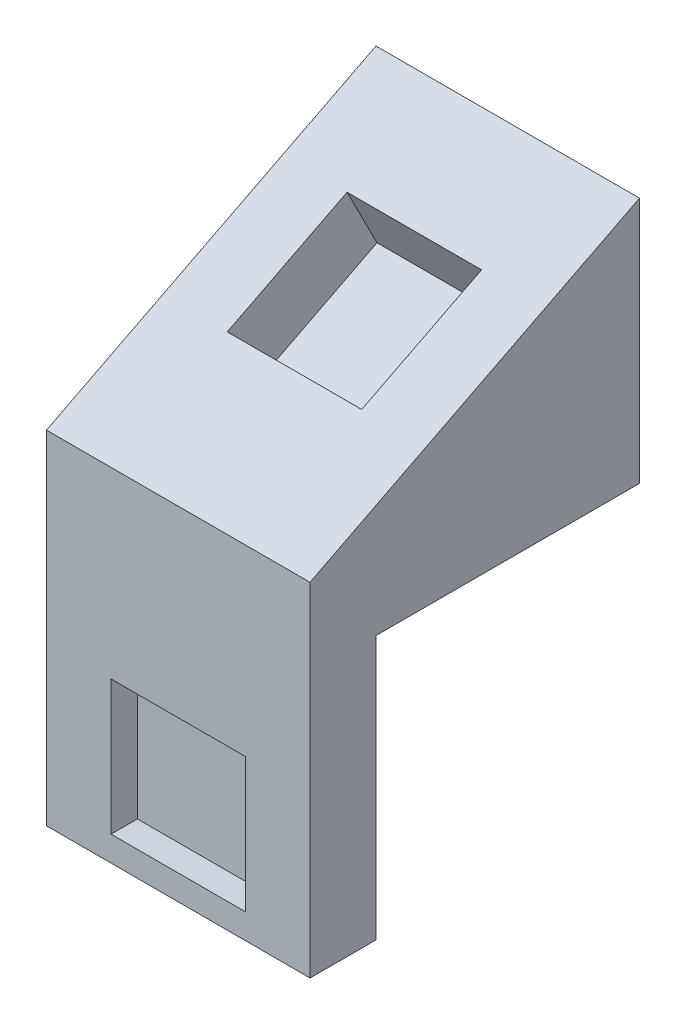
SolidWorks part; units mm, degrees
ref_plane "Płaszczyzna przednia" through (0, 0, 0) normal (0, 0, 1) x (1, 0, 0)
ref_plane "Płaszczyzna górna" through (0, 0, 0) normal (0, 1, 0) x (1, 0, 0)
ref_plane "Płaszczyzna prawa" through (0, 0, 0) normal (1, 0, 0) x (0, 0, -1)
sketch "Szkic1" plane through (0, 0, 0) normal (0, 0, 1) x (1, 0, 0)
  line L1 (-10, -13) -> (10, -13)
  line L2 (-10, -13) -> (-10, 13)
  line L3 (-10, 13) -> (10, 13)
  line L4 (10, -13) -> (10, 13)
  line L5 (-10, -13) -> (10, 13) construction
  line L6 (-10, 13) -> (10, -13) construction
  point P0 (0, 0)
  dimension "D1" = 26
  dimension "D2" = 20
extrude "Dodanie-wyciągnięcie1" add sketch "Szkic1" along normal blind 5
sketch "Szkic2" plane through (0, 0, 0) normal (0, 0, -1) x (-1, 0, 0)
  line L1 (10, 13) -> (-10, 13)
  line L2 (10, 13) -> (10, 7)
  line L3 (10, 7) -> (-10, 7)
  line L4 (-10, 13) -> (-10, 7)
  line L5 (-10, -13) -> (-10, 13) construction
  dimension "D1" = 6
  dimension "D2" = 20
extrude "Dodanie-wyciągnięcie2" add sketch "Szkic2" along normal blind 20
sketch "Szkic3" plane through (0, 0, 5) normal (0, 0, 1) x (1, 0, 0)
  line L0 (10, 13) -> (-10, 13) construction
  line L1 (-5.1, -11.1) -> (5.1, -11.1)
  line L2 (-5.1, -11.1) -> (-5.1, -0.9)
  line L3 (-5.1, -0.9) -> (5.1, -0.9)
  line L4 (5.1, -11.1) -> (5.1, -0.9)
  line L5 (-5.1, -11.1) -> (5.1, -0.9) construction
  line L6 (-5.1, -0.9) -> (5.1, -11.1) construction
  line L7 (-10, -13) -> (10, -13) construction
  point P0 (0, -6)
  point P7 (0, 13)
  dimension "D1" = 10.2
  dimension "D2" = 7
extrude "Wytnij-wyciągnięcie1" cut sketch "Szkic3" against normal blind 2
sketch "Szkic4" plane through (10, 0, 0) normal (1, 0, 0) x (0, 0, -1)
  line L0 (-5, 13) -> (20, 25.7381)
  line L1 (-5, 13) -> (20, 13) construction
  line L2 (20, 25.7381) -> (20, 13)
  line L3 (20, 13) -> (-5, 13)
  line L4 (-5, -13) -> (-5, 13) construction
  dimension "D1" = 27
extrude "Dodanie-wyciągnięcie3" add sketch "Szkic4" against normal up to surface (20 mm away) up to face at (-10, 2.3333, -5)
sketch "Szkic5" plane through (0, 12.3431, 6.2891) normal (0, 0.891, 0.454) x (1, 0, 0)
  line L0 (10, 1.4468) -> (-10, 1.4468) construction
  line L1 (-5.1, 11.3468) -> (5.1, 11.3468)
  line L2 (-5.1, 11.3468) -> (-5.1, 21.5468)
  line L3 (-5.1, 21.5468) -> (5.1, 21.5468)
  line L4 (5.1, 11.3468) -> (5.1, 21.5468)
  line L5 (-5.1, 11.3468) -> (5.1, 21.5468) construction
  line L6 (-5.1, 21.5468) -> (5.1, 11.3468) construction
  point P0 (0, 16.4468)
  dimension "D1" = 10.2
  dimension "D2" = 15
extrude "Wytnij-wyciągnięcie2" cut sketch "Szkic5" against normal blind 5
sketch "Szkic6" plane through (0, 0, -20) normal (0, 0, -1) x (-1, 0, 0)
  line L0 (-10, 7) -> (10, 7) construction
  circle A0 centre (0, 13) radius 2
  point P4 (0, 7)
  dimension "D1" = 4
  dimension "D2" = 6
extrude "Wytnij-wyciągnięcie3" cut sketch "Szkic6" against normal blind 6
